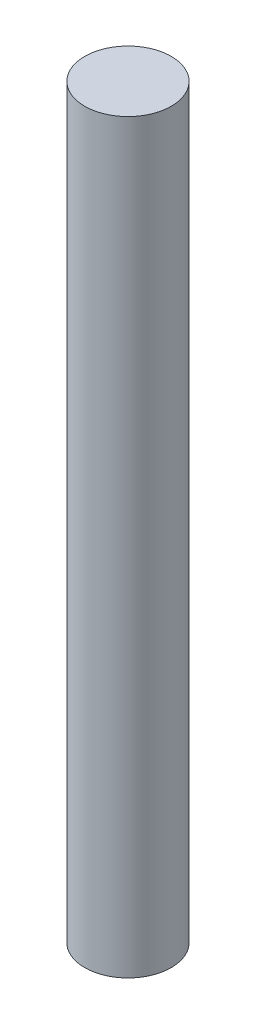
SolidWorks part; units mm, degrees
ref_plane "Front Plane" through (0, 0, 0) normal (0, 0, 1) x (1, 0, 0)
ref_plane "Top Plane" through (0, 0, 0) normal (0, 1, 0) x (1, 0, 0)
ref_plane "Right Plane" through (0, 0, 0) normal (1, 0, 0) x (0, 0, -1)
sketch "Sketch1" plane through (0, 0, 0) normal (0, 1, 0) x (1, 0, 0)
  circle A0 centre (0, 0) radius 4
extrude "Boss-Extrude1" add sketch "Sketch1" along normal blind 69
